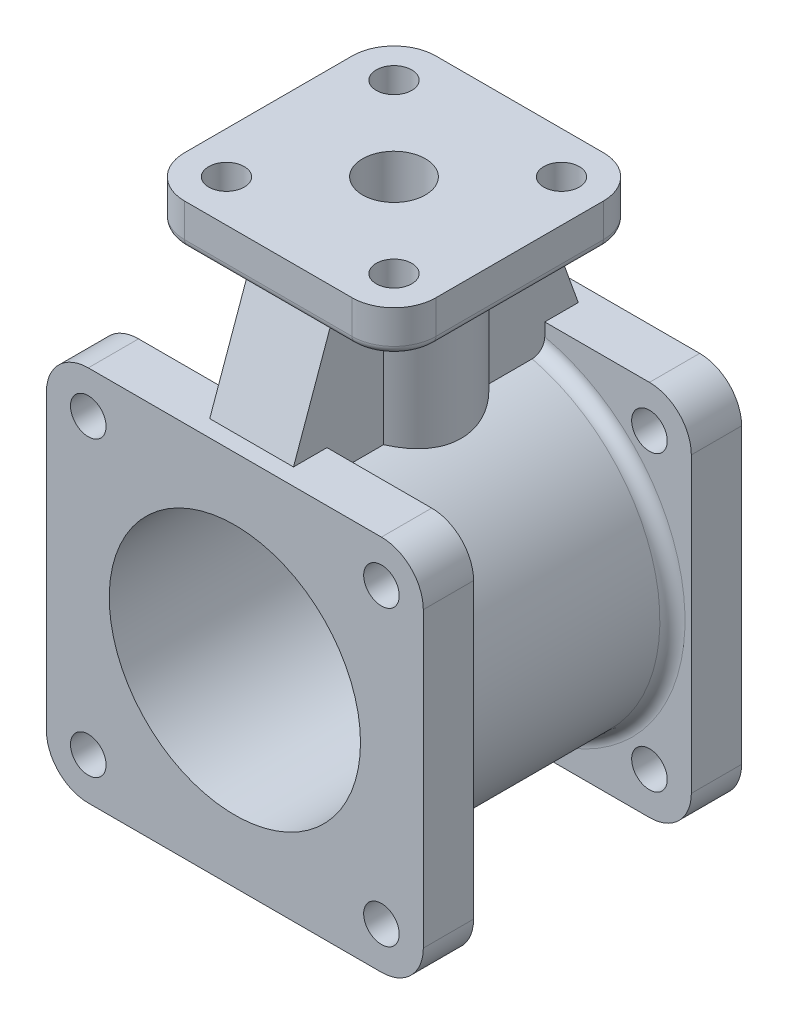
SolidWorks part; units mm, degrees
material "1.4000 (X6Cr13)"
ref_plane "前视基准面" through (0, 0, 0) normal (0, 0, 1) x (1, 0, 0)
ref_plane "上视基准面" through (0, 0, 0) normal (0, 1, 0) x (1, 0, 0)
ref_plane "右视基准面" through (0, 0, 0) normal (1, 0, 0) x (0, 0, -1)
other "Configuration Table"
sketch "草图8" plane through (0, 0, 0) normal (0, 0, 1) x (1, 0, 0)
  circle A0 centre (0.4902, 0) radius 40
  dimension "D1" = 80
extrude "凸台-拉伸3" add sketch "草图8" along normal mid plane 52
sketch "草图10" plane through (0, 0, 26) normal (0, 0, 1) x (1, 0, 0)
  line L1 (-35, -45) -> (35, -45)
  line L2 (-45, -35) -> (-45, 35)
  line L3 (-35, 45) -> (35, 45)
  line L4 (45, -35) -> (45, 35)
  line L5 (-45, -45) -> (45, 45) construction
  line L6 (-45, 45) -> (45, -45) construction
  arc A0 (35, -45) -> (45, -35) centre (35, -35) ccw
  arc A1 (-45, 35) -> (-35, 45) centre (-35, 35) cw
  arc A2 (-35, -45) -> (-45, -35) centre (-35, -35) cw
  arc A3 (35, 45) -> (45, 35) centre (35, 35) cw
  point P0 (0, 0)
  dimension "D2" = 10
  dimension "D1" = 90
extrude "凸台-拉伸4" add sketch "草图10" along normal blind 12
hole_wizard "M10 螺纹孔1" positions "草图13" profile "草图14" tap size "M10" standard "GB" end condition through all
sketch "草图13" plane through (0, 0, 38) normal (0, 0, 1) x (1, 0, 0)
  point P0 (-35, 35)
  point P3 (35, -35)
  point P6 (35, 35)
  point P9 (-35, -35)
sketch "草图14" plane through (-35, 35, 38) normal (1, 0, 0) x (0, -1, 0)
  line L0 (0, 0) -> (0, 64)
  line L1 (0, 64) -> (4.25, 64)
  line L2 (4.25, 64) -> (4.25, 0)
  line L5 (4.25, 0) -> (0, 0)
  line L11 (0, -6.35) -> (0, 107.95) construction
  dimension "通孔螺纹孔钻头直径" = 8.5
  dimension "通孔螺纹孔钻头深度" = 64
cosmetic thread "孔螺纹线1" parameters "D2"=10
cosmetic thread "孔螺纹线2" parameters "D2"=10
cosmetic thread "孔螺纹线3" parameters "D2"=10
cosmetic thread "孔螺纹线4" parameters "D2"=10
mirror "镜向1" about plane through (0, 0, 0) normal (0, 0, 1) of "凸台-拉伸4", "M10 螺纹孔1"
sketch "草图16" plane through (0, 0, 38) normal (0, 0, 1) x (1, 0, 0)
  circle A0 centre (0, 0) radius 30
extrude "切除-拉伸2" cut sketch "草图16" against normal through all both and the other way through all
ref_plane "基准面1" through (0, 83, 0) normal (0, 1, 0) x (1, 0, 0)
sketch "草图17" plane through (0, 83, 0) normal (0, 1, 0) x (1, 0, 0)
  line L1 (-20, -30) -> (20, -30)
  line L2 (-30, -20) -> (-30, 20)
  line L3 (-20, 30) -> (20, 30)
  line L4 (30, -20) -> (30, 20)
  line L5 (-30, -30) -> (30, 30) construction
  line L6 (-30, 30) -> (30, -30) construction
  arc A0 (20, -30) -> (30, -20) centre (20, -20) ccw
  arc A1 (-30, 20) -> (-20, 30) centre (-20, 20) cw
  arc A2 (-20, -30) -> (-30, -20) centre (-20, -20) cw
  arc A3 (20, 30) -> (30, 20) centre (20, 20) cw
  point P0 (0, 0)
  point P8 (20, -20)
  point P11 (-20, 20)
  point P14 (-20, -20)
  point P17 (20, 20)
  dimension "D2" = 10
  dimension "D1" = 60
extrude "凸台-拉伸6" add sketch "草图17" against normal blind 10 separate body
hole_wizard "M10 螺纹孔3" positions "草图19" profile "草图20" tap size "M10" standard "GB" end condition up to next
sketch "草图19" plane through (0, 83, 0) normal (0, 1, 0) x (1, 0, 0)
  point P0 (-20, 20)
  point P8 (20, 20)
  point P13 (-20, -20)
  point P16 (20, -20)
sketch "草图20" plane through (-20, 83, -20) normal (1, 0, 0) x (0, 0, 1)
  line L0 (0, 0) -> (0, 60.6393)
  line L1 (0, 60.6393) -> (4.25, 60.6393)
  line L2 (4.25, 60.6393) -> (4.25, 0)
  line L5 (4.25, 0) -> (0, 0)
  line L11 (0, -6.35) -> (0, 107.95) construction
  dimension "通孔螺纹孔钻头直径" = 8.5
  dimension "通孔螺纹孔钻头深度" = 60.6393
cosmetic thread "孔螺纹线10" parameters "D2"=10
cosmetic thread "孔螺纹线11" parameters "D2"=10
cosmetic thread "孔螺纹线12" parameters "D2"=10
cosmetic thread "孔螺纹线13" parameters "D2"=10
sketch "草图21" plane through (0, 83, 0) normal (0, 1, 0) x (1, 0, 0)
  circle A0 centre (0, 0) radius 16
  dimension "D1" = 32
extrude "凸台-拉伸7" add sketch "草图21" against normal up to surface (43.003 mm away)
sketch "草图22" plane through (0, 83, 0) normal (0, 1, 0) x (1, 0, 0)
  circle A0 centre (0, 0) radius 7.5
  dimension "D1" = 15
extrude "切除-拉伸3" cut sketch "草图22" against normal up to next and the other way through all
sketch "草图27" plane through (0, 0, 0) normal (1, 0, 0) x (0, 0, -1)
  line L0 (-24, 73) -> (-34, 45)
  line L1 (-30, 73) -> (-20, 73) construction
  line L3 (0, 0) -> (0, 83) construction
  line L4 (36.3438, 83) -> (-36.3438, 83) construction
  line L7 (-38, 45) -> (-26, 45) construction
  point P4 (-36.2777, 45)
  point P11 (-38, 45)
  point P12 (-38, 53.6432)
  point P13 (-38, 45)
  point P14 (-38, 45)
  point P15 (-38, 45)
  point P16 (0, 0)
  point P17 (0, 0)
  point P18 (0, 0)
  point P19 (0, 0)
  dimension "D1" = 48
  dimension "D2" = 68
rib "筋1" sketch "草图27" sketch "草图27" thickness 20 extrusion direction parallel to sketch draft on no parameters "D1"=20
mirror "镜向2" about plane through (0, 0, 0) normal (0, 0, 1) of "筋1"
fillet "圆角1" radius 2 20 edges at (20, 73, 24.25) (-20, 73, 24.25) (20, 73, -15.75) (-20, 73, -15.75) (30, 73, 0) (27.0711, 73, -27.0711) (0, 73, -30) (-27.0711, 73, -27.0711) (-30, 73, 0) (-27.0711, 73, 27.0711) (0, 73, 30) (27.0711, 73, 27.0711) (-10, 73, 18.245) (-16, 73, 0) (-10, 73, -18.245) (0, 73, -24) (10, 73, -18.245) (16, 73, 0) (10, 73, 18.245) (0, 73, 24)
fillet "圆角4" radius 3 2 edges at (0.9966, -39.9968, -26) (0.9966, -39.9968, 26)
